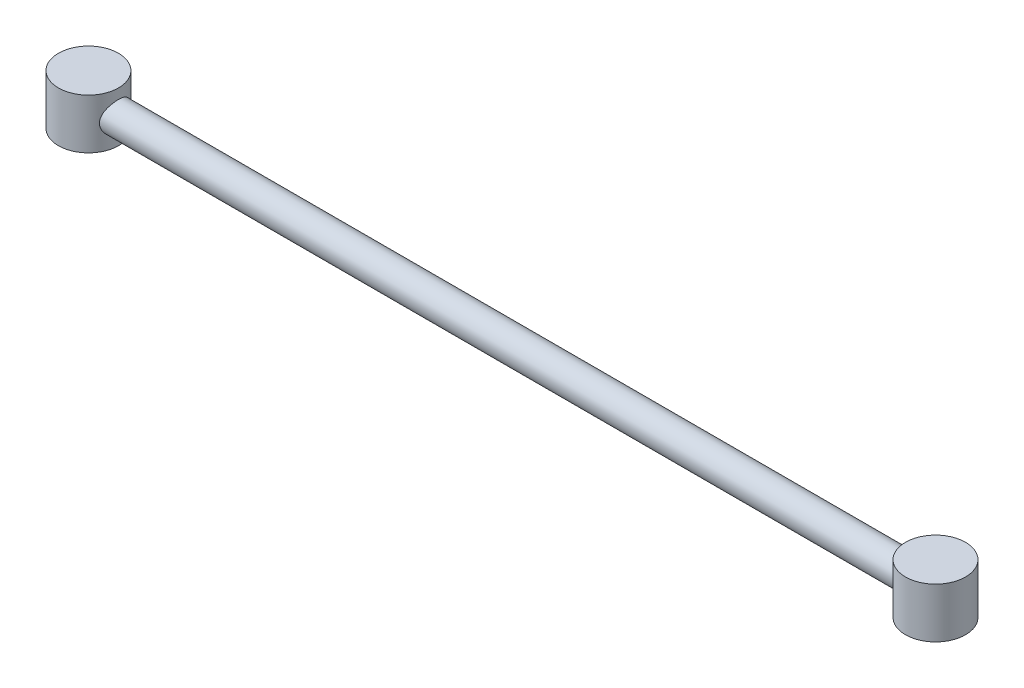
SolidWorks part; units mm, degrees
ref_plane "Front Plane" through (0, 0, 0) normal (0, 0, 1) x (1, 0, 0)
ref_plane "Top Plane" through (0, 0, 0) normal (0, 1, 0) x (1, 0, 0)
ref_plane "Right Plane" through (0, 0, 0) normal (1, 0, 0) x (0, 0, -1)
sketch "Sketch1" plane through (0, 0, 0) normal (0, 1, 0) x (1, 0, 0)
  line L0 (-268.478, 0) -> (0, 0) construction
  circle A0 centre (-268.478, 0) radius 19.05
  dimension "D1" = 268.478
  dimension "D2" = 38.1
extrude "Boss-Extrude1" add sketch "Sketch1" along normal mid plane 31.75
sketch "Sketch3" plane through (0, 0, 0) normal (1, 0, 0) x (0, 0, -1)
  circle A0 centre (0, 0) radius 9.525
  dimension "D1" = 19.05
extrude "Boss-Extrude2" add sketch "Sketch3" against normal up to next
mirror "Mirror3" about plane through (0, 0, 0) normal (1, 0, 0) of bodies 102
sketch "Sketch4" plane through (0, -15.875, 0) normal (0, -1, 0) x (1, 0, 0)
  line L0 (-37.3685, 0) -> (22.3042, 0) construction
  line L1 (-281.178, 0) -> (-255.778, 0)
  line L2 (255.778, 0) -> (281.178, 0)
  arc A0 (-255.778, 0) -> (-281.178, 0) centre (-268.478, 0) ccw
  arc A1 (281.178, 0) -> (255.778, 0) centre (268.478, 0) ccw
  dimension "D1" = 25.4
revolve "Cut-Revolve1" cut sketch "Sketch4" angle 360 about L0
sketch "Sketch5" plane through (0, 0, 0) normal (1, 0, 0) x (0, 0, -1)
  line L1 (0, -1.27) -> (13.408, -1.27)
  line L2 (0, -1.27) -> (0, 1.27)
  line L3 (0, 1.27) -> (13.408, 1.27)
  line L4 (13.408, -1.27) -> (13.408, 1.27)
  dimension "D1" = 2.54
extrude "Cut-Extrude2" cut sketch "Sketch5" against normal mid plane 6.35
sketch "Sketch6" plane through (0, -1.27, 0) normal (0, 1, 0) x (1, 0, 0)
  circle A0 centre (0, 6.2917) radius 1.27
  dimension "D1" = 2.54
extrude "Boss-Extrude3" add sketch "Sketch6" along normal up to next
